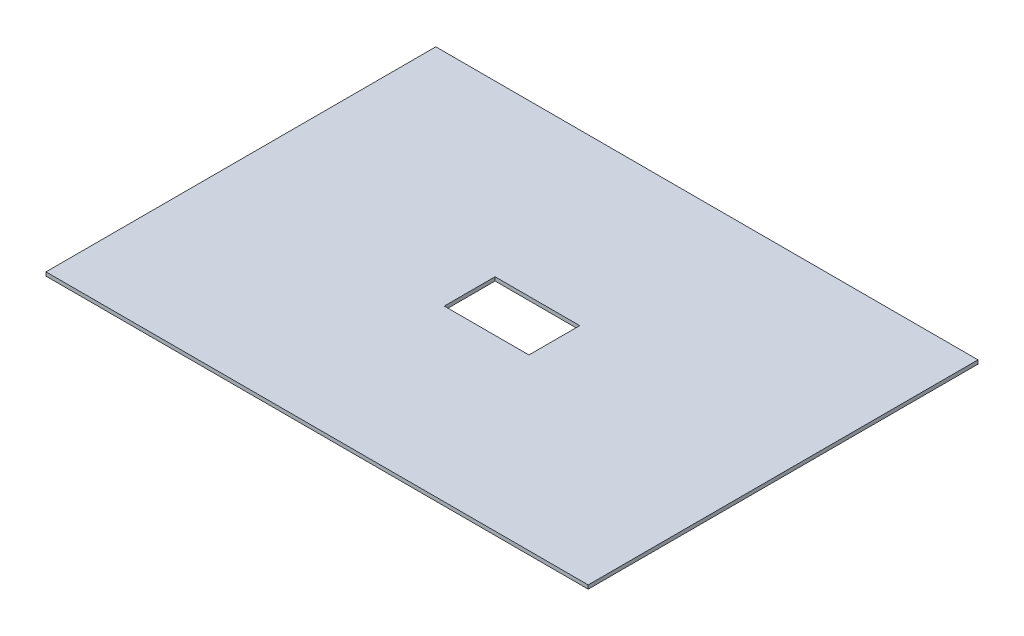
SolidWorks part; units mm, degrees
ref_plane "前视基准面" through (0, 0, 0) normal (0, 0, 1) x (1, 0, 0)
ref_plane "上视基准面" through (0, 0, 0) normal (0, 1, 0) x (1, 0, 0)
ref_plane "右视基准面" through (0, 0, 0) normal (1, 0, 0) x (0, 0, -1)
other "Configuration Table"
sketch "草图1" plane through (0, 0, 0) normal (0, 1, 0) x (1, 0, 0)
  line L1 (0, 0) -> (320.2, 0)
  line L2 (0, 0) -> (0, -230.2)
  line L3 (0, -230.2) -> (320.2, -230.2)
  line L4 (320.2, 0) -> (320.2, -230.2)
  dimension "D1" = 320.2
  dimension "D2" = 230.2
extrude "凸台-拉伸1" add sketch "草图1" along normal blind 2.2
sketch "草图2" plane through (0, 2.2, 0) normal (0, 1, 0) x (1, 0, 0)
  line L0 (0, 0) -> (0, -230.2) construction
  line L1 (135.1, -100.1) -> (185.1, -100.1)
  line L2 (135.1, -100.1) -> (135.1, -130.1)
  line L3 (135.1, -130.1) -> (185.1, -130.1)
  line L4 (185.1, -100.1) -> (185.1, -130.1)
  line L6 (160.1, 0) -> (160.1, -99.9878) construction
  line L7 (320.2, 0) -> (0, 0) construction
  line L8 (160.1, -100.1) -> (160.1, -99.9878) construction
  point P8 (0, -115.1)
  point P9 (135.1, -115.1)
  dimension "D3" = 30
  dimension "D4" = 50
extrude "切除-拉伸1" cut sketch "草图2" against normal through all
